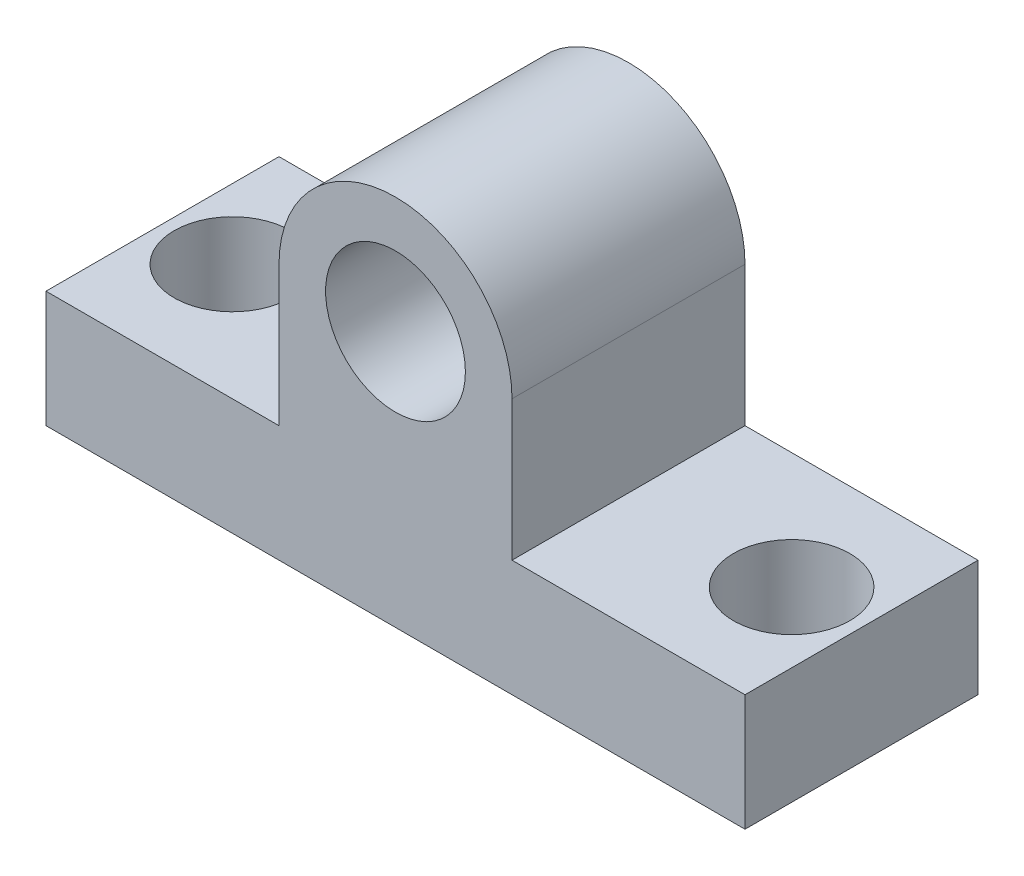
SolidWorks part; units mm, degrees
ref_plane "前视基准面" through (0, 0, 0) normal (0, 0, 1) x (1, 0, 0)
ref_plane "上视基准面" through (0, 0, 0) normal (0, 1, 0) x (1, 0, 0)
ref_plane "右视基准面" through (0, 0, 0) normal (1, 0, 0) x (0, 0, -1)
sketch "草图1" plane through (0, 0, 0) normal (0, 0, 1) x (1, 0, 0)
  line L0 (5, 0) -> (15, 0)
  line L1 (15, 0) -> (15, -5)
  line L2 (15, -5) -> (-15, -5)
  line L4 (5, 6) -> (5, 0)
  line L5 (-15, 0) -> (-15, -5)
  line L6 (-5, 0) -> (-15, 0)
  line L7 (-5, 6) -> (-5, 0)
  arc A0 (5, 6) -> (-5, 6) centre (0, 6) ccw
  circle A1 centre (0, 6) radius 3
  point P11 (0, -5)
  dimension "D3" = 10
  dimension "D4" = 6
  dimension "D1" = 6
  dimension "D2" = 5
extrude "凸台-拉伸1" add sketch "草图1" along normal blind 10
sketch "草图2" plane through (0, 0, 0) normal (0, 1, 0) x (1, 0, 0)
  line L0 (-5, 0) -> (-15, 0) construction
  line L4 (-15, -10) -> (-15, 0) construction
  circle A0 centre (-12, -5) radius 2.5
  dimension "D1" = 5
  dimension "D2" = 3
extrude "切除-拉伸1" cut sketch "草图2" against normal blind 5 contours A0
sketch "草图3" plane through (0, 0, 0) normal (0, 1, 0) x (1, 0, 0)
  line L0 (15, -10) -> (15, 0) construction
  line L1 (15, -10) -> (5, -10) construction
  circle A0 centre (12, -5) radius 2.5
  dimension "D1" = 3
  dimension "D2" = 5
  dimension "D3" = 5
extrude "切除-拉伸2" cut sketch "草图3" against normal blind 5 contours A0
